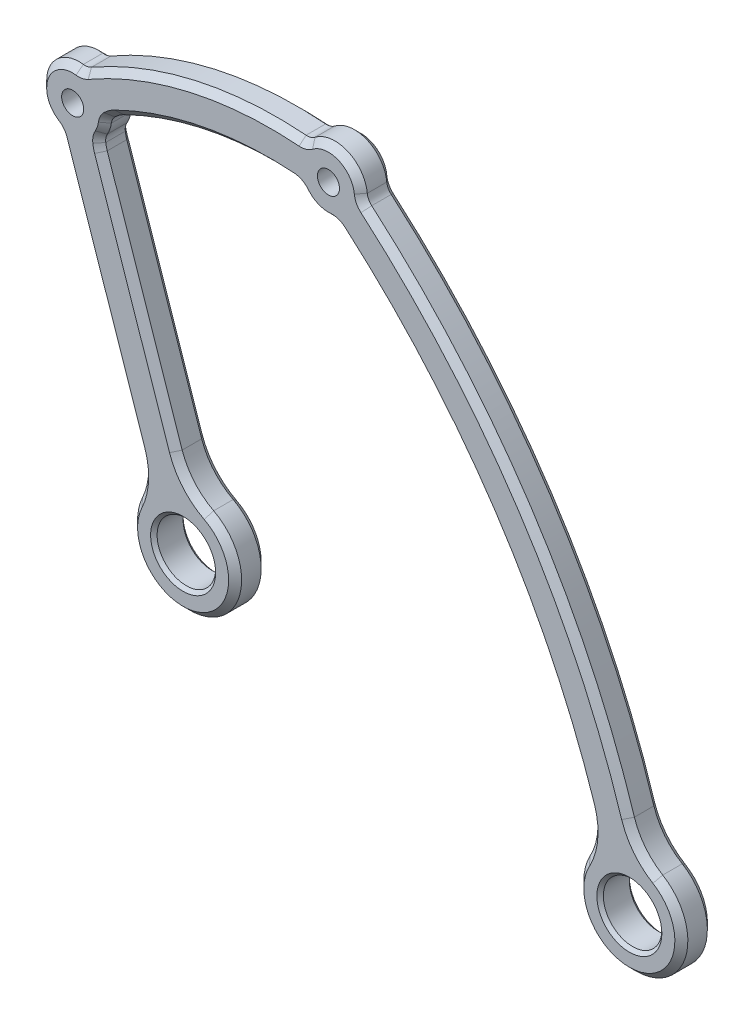
SolidWorks part; units mm, degrees
material "A2017"
ref_plane "正面" through (0, 0, 0) normal (0, 0, 1) x (1, 0, 0)
ref_plane "平面" through (0, 0, 0) normal (0, 1, 0) x (1, 0, 0)
ref_plane "右側面" through (0, 0, 0) normal (1, 0, 0) x (0, 0, -1)
sketch "ｽｹｯﾁ2" plane through (0, 0, 0) normal (0, 0, 1) x (1, 0, 0)
  line L4 (-103.4721, 101.9749) -> (-90.4656, 63.494)
  line L5 (-84.7815, 65.4152) -> (-96.3061, 99.5117)
  circle A0 centre (-91.0319, 74.5383) radius 1 construction
  circle A1 centre (-100.6248, 104.2316) radius 1
  circle A2 centre (-61.2846, 113.3479) radius 1
  circle A3 centre (-27.0948, 71.9322) radius 1 construction
  circle A21 centre (-100.6248, 104.2316) radius 1.5 construction
  circle A22 centre (-61.2846, 113.3479) radius 1.5 construction
  circle A23 centre (-91.0319, 74.5383) radius 1.5 construction
  circle A24 centre (-83.6371, 52.6602) radius 4.5
  circle A25 centre (-27.0948, 71.9322) radius 1.5 construction
  circle A26 centre (-15, 38.9143) radius 4.5
  arc A30 (-15.2219, 51.2935) -> (-57.8253, 114.4005) centre (-143.6936, 10.4967) ccw
  arc A31 (-57.8253, 114.4005) -> (-62.9665, 116.6163) centre (-64.1956, 106.6922) ccw
  arc A32 (-62.9665, 116.6163) -> (-64.6165, 116.798) centre (-70.4705, 56.0286) ccw
  arc A33 (-64.6165, 116.798) -> (-101.462, 107.7671) centre (-70.1265, 59.5994) ccw
  arc A34 (-101.462, 107.7671) -> (-103.4721, 101.9749) centre (-98.7354, 103.5759) ccw
  arc A35 (-90.8824, 56.0521) -> (-90.4656, 63.494) centre (-99.9391, 60.2919) ccw
  arc A36 (-90.8824, 56.0521) -> (-79.9353, 59.7522) centre (-83.6371, 52.6602) ccw
  arc A37 (-84.7815, 65.4152) -> (-79.9353, 59.7522) centre (-75.308, 68.6172) ccw
  arc A38 (-93.7791, 105.5979) -> (-96.3061, 99.5117) centre (-91.5694, 101.1127) ccw
  arc A39 (-65.8029, 110.8809) -> (-93.7791, 105.5979) centre (-70.2884, 57.9186) ccw
  arc A40 (-60.161, 108.5281) -> (-65.8029, 110.8809) centre (-66.6468, 100.9166) ccw
  arc A41 (-21.3117, 50.6279) -> (-60.161, 108.5281) centre (-143.6936, 10.4967) ccw
  arc A42 (-22.0284, 42.7355) -> (-21.3117, 50.6279) centre (-30.8139, 47.512) ccw
  arc A43 (-22.0284, 42.7355) -> (-10.8626, 45.7613) centre (-15, 38.9143) ccw
  arc A44 (-15.2219, 51.2935) -> (-10.8626, 45.7613) centre (-5.6909, 54.3201) ccw
  dimension "D1" = 9
  dimension "D2" = 2
extrude "ﾎﾞｽ - 押し出し1" add sketch "ｽｹｯﾁ2" along normal blind 5
hole_wizard "M3 すきま穴1" positions "ｽｹｯﾁ3" profile "ｽｹｯﾁ4" hole size "M3" standard "JIS" end condition through all
sketch "ｽｹｯﾁ3" plane through (0, 0, 5) normal (0, 0, 1) x (1, 0, 0)
  point P3 (-100.6248, 104.2316)
  point P6 (-61.2846, 113.3479)
sketch "ｽｹｯﾁ4" plane through (-100.6248, 104.2316, 5) normal (1, 0, 0) x (0, -1, 0)
  line L0 (0, 0) -> (0, 5)
  line L1 (0, 5) -> (1.7, 5)
  line L2 (1.7, 5) -> (1.7, 0)
  line L5 (1.7, 0) -> (0, 0)
  line L11 (0, -6.35) -> (0, 107.95) construction
  dimension "通し穴の直径" = 3.4
  dimension "通し穴の深さ" = 5
sketch "ｽｹｯﾁ5" plane through (0, 0, 5) normal (0, 0, 1) x (1, 0, 0)
  circle A3 centre (-61.2846, 113.3479) radius 5
  circle A5 centre (-100.6248, 104.2316) radius 5
  circle A6 centre (-61.2846, 113.3479) radius 1.7 construction
  circle A7 centre (-100.6248, 104.2316) radius 1.7 construction
  circle A8 centre (-61.2846, 113.3479) radius 1.7
  circle A9 centre (-100.6248, 104.2316) radius 1.7
  dimension "D1" = 10
extrude "ﾎﾞｽ - 押し出し2" add sketch "ｽｹｯﾁ5" against normal up to surface (5 mm away) up to face at (-98.9248, 104.2316, 0)
fillet "ﾌｨﾚｯﾄ1" radius 2 8 edges at (-65.6241, 110.8642, 2.5) (-60.1129, 108.4871, 2.5) (-64.8798, 116.8227, 2.5) (-99.3623, 109.0696, 2.5) (-102.6969, 99.6812, 2.5) (-95.6288, 104.0317, 2.5) (-96.5654, 101.3126, 2.5) (-56.2902, 113.1125, 2.5)
chamfer "面取り1" distance 1 angle 45 52 edges at (-94.4873, 105.1729, 5) (-94.4873, 105.1729, 0) (-80.5382, 110.0729, 0) (-80.5382, 110.0729, 5) (-95.4866, 104.1209, 5) (-95.4866, 104.1209, 0) (-65.8037, 110.7202, 0) (-65.8037, 110.7202, 5) (-95.8974, 102.6034, 0) (-95.8974, 102.6034, 5) (-63.2544, 108.7523, 0) (-63.2544, 108.7523, 5) (-96.5082, 101.1547, 0) (-96.5082, 101.1547, 5) (-60.0968, 108.2716, 5) (-60.0968, 108.2716, 0) (-96.4462, 100.0097, 0) (-96.4462, 100.0097, 5) (-36.4686, 81.8454, 5) (-36.4686, 81.8454, 0) (-90.5438, 82.4634, 0) (-90.5438, 82.4634, 5) (-20.8549, 46.6077, 0) (-20.8549, 46.6077, 5) (-82.9057, 62.1153, 0) (-82.9057, 62.1153, 5) (-12.9075, 31.1928, 0) (-12.9075, 31.1928, 5) (-81.0755, 45.0814, 0) (-81.0755, 45.0814, 5) (-13.5454, 48.1309, 0) (-13.5454, 48.1309, 5) (-89.9548, 59.7327, 0) (-89.9548, 59.7327, 5) (-31.1766, 84.7213, 0) (-31.1766, 84.7213, 5) (-96.456, 81.217, 5) (-96.456, 81.217, 0) (-56.0945, 113.1345, 0) (-56.0945, 113.1345, 5) (-102.7716, 99.5392, 5) (-102.7716, 99.5392, 0) (-59.3114, 117.9421, 0) (-59.3114, 117.9421, 5) (-105.3313, 105.9196, 0) (-105.3313, 105.9196, 5) (-64.9912, 116.9712, 5) (-64.9912, 116.9712, 0) (-99.3345, 109.2117, 0) (-99.3345, 109.2117, 5) (-82.7842, 115.6513, 5) (-82.7842, 115.6513, 0)
chamfer "面取り2" distance 0.5 angle 45 4 edges at (-79.1371, 52.6602, 5) (-79.1371, 52.6602, 0) (-10.5, 38.9143, 5) (-10.5, 38.9143, 0)
